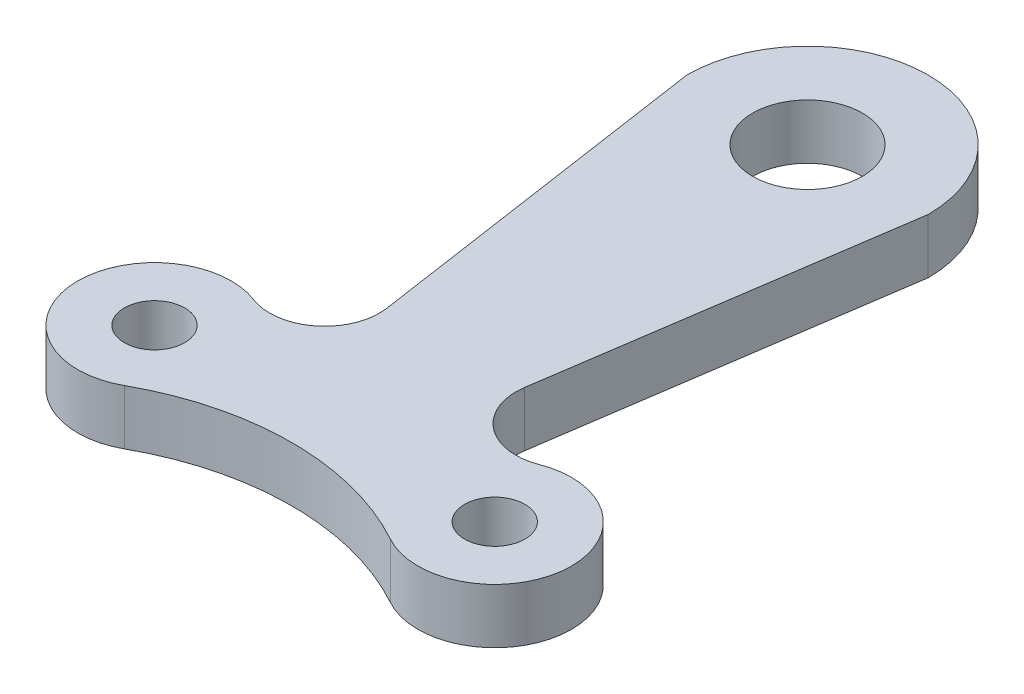
SolidWorks part; units mm, degrees
ref_plane "Front Plane" through (0, 0, 0) normal (0, 0, 1) x (1, 0, 0)
ref_plane "Top Plane" through (0, 0, 0) normal (0, 1, 0) x (1, 0, 0)
ref_plane "Right Plane" through (0, 0, 0) normal (1, 0, 0) x (0, 0, -1)
sketch "Sketch1" plane through (0, 0, 0) normal (0, 1, 0) x (1, 0, 0)
  line L6 (-22, 0) -> (-12.527, -64.1248)
  line L7 (22, 0) -> (12.5267, -64.1267)
  circle A0 centre (0, 0) radius 10
  arc A1 (22, 0) -> (-22, 0) centre (0, 0) ccw
  circle A2 centre (31, -88) radius 5.5
  circle A4 centre (-31, -88) radius 5.5
  arc A5 (24.2198, -100.2467) -> (25.9949, -74.9271) centre (31, -88) ccw
  arc A6 (-25.9948, -74.9253) -> (-24.2184, -100.2478) centre (-31, -88) ccw
  arc A7 (24.2198, -100.2467) -> (-24.2184, -100.2478) centre (0.0018, -143.9901) ccw
  arc A8 (-25.9948, -74.9253) -> (-12.527, -64.1248) centre (-22.4197, -65.5862) ccw
  arc A9 (12.5267, -64.1267) -> (25.9949, -74.9271) centre (22.4194, -65.5882) ccw
  point P0 (0, 0)
  dimension "D1" = 20
  dimension "D6" = 27.9966
  dimension "D7" = 28
extrude "Boss-Extrude1" add sketch "Sketch1" along normal blind 10
